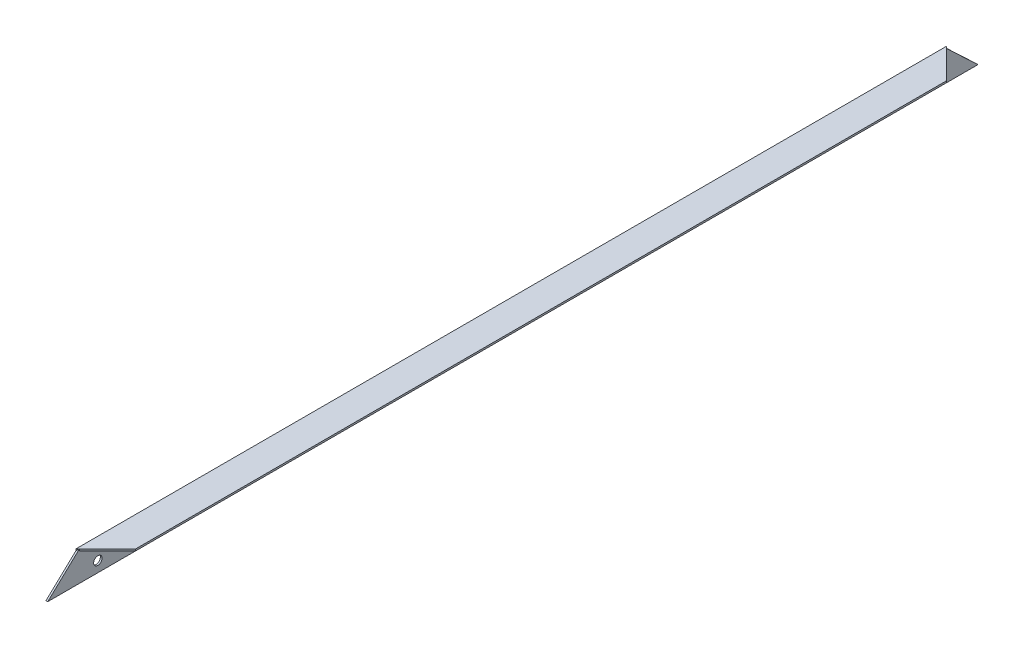
SolidWorks part; units mm, degrees
material "Ст 3 ГОСТ 380-88"
ref_plane "Front Plane" through (0, 0, 0) normal (0, 0, 1) x (1, 0, 0)
ref_plane "Top Plane" through (0, 0, 0) normal (0, 1, 0) x (1, 0, 0)
ref_plane "Right Plane" through (0, 0, 0) normal (1, 0, 0) x (0, 0, -1)
sketch "Sketch1" plane through (0, 0, 0) normal (0, 0, 1) x (1, 0, 0)
  line L0 (0, 42.7885) -> (0, -29.0064) construction
  line L1 (-43.5897, 0) -> (38.7821, 0) construction
  line L2 (-17.9063, 20.1835) -> (-17.9063, -22.3165)
  line L3 (-17.9063, -22.3165) -> (-15.4063, -22.3165)
  line L4 (-15.4063, -22.3165) -> (-15.4063, 17.6835)
  line L5 (-15.4063, 17.6835) -> (24.5937, 17.6835)
  line L6 (24.5937, 17.6835) -> (24.5937, 20.1835)
  line L7 (24.5937, 20.1835) -> (-17.9063, 20.1835)
  dimension "D1" = 40
  dimension "D2" = 40
  dimension "D3" = 2.5
extrude "Boss-Extrude1" add sketch "Sketch1" along normal mid plane 1237.5
sketch "Sketch2" plane through (0, 20.1835, 0) normal (0, 1, 0) x (1, 0, 0)
  line L0 (-17.9063, 618.75) -> (24.5937, 576.25)
  line L1 (24.5937, -618.75) -> (24.5937, 618.75) construction
  line L2 (24.5937, 576.25) -> (24.5937, 618.75)
  line L3 (24.5937, 618.75) -> (-17.9063, 618.75) construction
  line L4 (24.5937, 618.75) -> (-17.9063, 618.75)
  line L5 (-352.1646, 0) -> (379.6583, 0) construction
  line L6 (24.5937, -576.25) -> (24.5937, -618.75)
  line L7 (-17.9063, -618.75) -> (24.5937, -576.25)
  line L8 (24.5937, -618.75) -> (-17.9063, -618.75)
  dimension "D1" = 42.5
extrude "Cut-Extrude1" cut sketch "Sketch2" against normal blind 10
sketch "Sketch3" plane through (-15.4063, 0, 0) normal (1, 0, 0) x (0, 0, -1)
  line L0 (-616.25, 20.1835) -> (-661.25, -22.3165)
  line L1 (-661.25, -22.3165) -> (-616.25, -22.3165)
  line L2 (0, 129.8861) -> (0, -136.0154) construction
  line L3 (-616.25, 20.1835) -> (-616.25, -22.3165)
  line L4 (616.25, 20.1835) -> (661.25, -22.3165)
  line L5 (661.25, -22.3165) -> (616.25, -22.3165)
  line L6 (616.25, 20.1835) -> (616.25, -22.3165)
  line L8 (-618.75, -22.3165) -> (-618.75, 10.1835) construction
  dimension "D1" = 45
  dimension "D2" = 2.5
extrude "Boss-Extrude5" add sketch "Sketch3" against normal blind 2.5
sketch "Sketch5" plane through (-15.4063, 0, 0) normal (1, 0, 0) x (0, 0, -1)
  line L0 (-661.25, -22.3165) -> (661.25, -22.3165) construction
  circle A0 centre (-590, -7.3165) radius 6
  circle A1 centre (-472, -7.3165) radius 6
  circle A2 centre (-354, -7.3165) radius 6
  circle A3 centre (-236, -7.3165) radius 6
  circle A4 centre (-118, -7.3165) radius 6
  circle A5 centre (0, -7.3165) radius 6
  circle A6 centre (118, -7.3165) radius 6
  circle A7 centre (236, -7.3165) radius 6
  circle A8 centre (354, -7.3165) radius 6
  circle A9 centre (472, -7.3165) radius 6
  circle A10 centre (590, -7.3165) radius 6
  dimension "D1" = 590
  dimension "D3" = 12
  dimension "D2" = 15
  dimension "D4" = 11
  dimension "D5" = 590
extrude "Cut-Extrude2" cut sketch "Sketch5" against normal through all both and the other way through all
equation "\"D4\"=6.33004"
